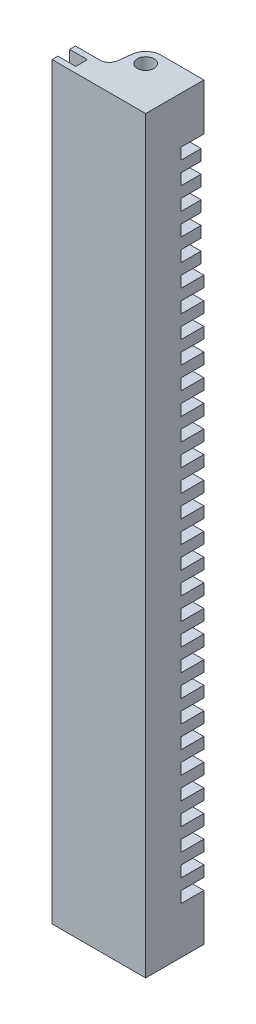
SolidWorks part; units mm, degrees
ref_plane "Front Plane" through (0, 0, 0) normal (0, 0, 1) x (1, 0, 0)
ref_plane "Top Plane" through (0, 0, 0) normal (0, 1, 0) x (1, 0, 0)
ref_plane "Right Plane" through (0, 0, 0) normal (1, 0, 0) x (0, 0, -1)
sketch "Sketch1" plane through (0, 0, 0) normal (0, 1, 0) x (1, 0, 0)
  line L0 (0, 0) -> (25.4, 0)
  line L1 (25.4, 0) -> (25.4, 25.4)
  line L2 (25.4, 25.4) -> (19.05, 25.4)
  line L3 (19.05, 25.4) -> (19.05, 6.35)
  line L4 (19.05, 6.35) -> (0, 6.35)
  line L5 (0, 6.35) -> (0, 0)
  dimension "D1" = 25.4
  dimension "D2" = 6.35
extrude "Boss-Extrude1" add sketch "Sketch1" along normal blind 203.2
sketch "Sketch2" plane through (0, 203.2, 0) normal (0, 1, 0) x (1, 0, 0)
  line L0 (19.05, 25.4) -> (19.05, 6.35) construction
  line L1 (19.05, 6.35) -> (0, 6.35) construction
  line L2 (19.05, 15.8022) -> (19.05, 6.35)
  line L3 (19.05, 6.35) -> (8.89, 6.35)
  line L4 (8.89, 6.35) -> (9.6295, 12.244)
  line L5 (19.05, 15.8022) -> (13.6618, 15.8022)
  line L6 (13.6618, 11.7382) -> (19.05, 6.35) construction
  arc A0 (13.6618, 15.8022) -> (9.6295, 12.244) centre (13.6618, 11.7382) ccw
  circle A1 centre (13.6618, 11.7382) radius 2.286
  dimension "D4" = 4.572
  dimension "D5" = 1.778
  dimension "D1" = 45
  dimension "D3" = 10.16
  dimension "D6" = 7.62
extrude "Boss-Extrude2" add sketch "Sketch2" against normal blind 6.35
ref_plane "Plane1" through (0, 101.6, 0) normal (0, 1, 0) x (1, 0, 0)
fillet "Fillet1" radius 2.54 1 edges at (8.89, 200.025, -6.35)
mirror "Mirror1" about plane through (0, 101.6, 0) normal (0, 1, 0) of "Fillet1", "Boss-Extrude2"
sketch "Sketch5" plane through (0, 203.2, 0) normal (0, 1, 0) x (1, 0, 0)
  line L0 (25.4, 0) -> (25.4, 25.4) construction
  line L1 (19.05, 25.4) -> (25.4, 25.4)
  line L2 (19.05, 25.4) -> (19.05, 15.8022)
  line L3 (19.05, 15.8022) -> (25.4, 15.8022)
  line L4 (25.4, 25.4) -> (25.4, 15.8022)
extrude "Cut-Extrude3" cut sketch "Sketch5" against normal through all
sketch "Sketch3" plane through (19.05, 0, 0) normal (-1, 0, 0) x (0, 0, 1)
  line L1 (-15.8022, 190.5) -> (-9.525, 190.5)
  line L2 (-15.8022, 190.5) -> (-15.8022, 187.452)
  line L3 (-15.8022, 187.452) -> (-9.525, 187.452)
  line L4 (-9.525, 190.5) -> (-9.525, 187.452)
  line L5 (-6.35, 196.85) -> (-6.35, 6.35) construction
  line L7 (-15.8022, 184.4741) -> (-15.8022, 181.4261)
  line L8 (-15.8022, 184.4741) -> (-9.525, 184.4741)
  line L9 (-9.525, 184.4741) -> (-9.525, 181.4261)
  line L10 (-15.8022, 181.4261) -> (-9.525, 181.4261)
  line L11 (-15.8022, 178.4481) -> (-15.8022, 175.4001)
  line L12 (-15.8022, 178.4481) -> (-9.525, 178.4481)
  line L13 (-9.525, 178.4481) -> (-9.525, 175.4001)
  line L14 (-15.8022, 175.4001) -> (-9.525, 175.4001)
  line L15 (-15.8022, 172.4222) -> (-15.8022, 169.3742)
  line L16 (-15.8022, 172.4222) -> (-9.525, 172.4222)
  line L17 (-9.525, 172.4222) -> (-9.525, 169.3742)
  line L18 (-15.8022, 169.3742) -> (-9.525, 169.3742)
  line L19 (-15.8022, 166.3963) -> (-15.8022, 163.3483)
  line L20 (-15.8022, 166.3963) -> (-9.525, 166.3963)
  line L21 (-9.525, 166.3963) -> (-9.525, 163.3483)
  line L22 (-15.8022, 163.3483) -> (-9.525, 163.3483)
  line L23 (-15.8022, 160.3703) -> (-15.8022, 157.3223)
  line L24 (-15.8022, 160.3703) -> (-9.525, 160.3703)
  line L25 (-9.525, 160.3703) -> (-9.525, 157.3223)
  line L26 (-15.8022, 157.3223) -> (-9.525, 157.3223)
  line L27 (-15.8022, 154.3444) -> (-15.8022, 151.2964)
  line L28 (-15.8022, 154.3444) -> (-9.525, 154.3444)
  line L29 (-9.525, 154.3444) -> (-9.525, 151.2964)
  line L30 (-15.8022, 151.2964) -> (-9.525, 151.2964)
  line L31 (-15.8022, 148.3185) -> (-15.8022, 145.2705)
  line L32 (-15.8022, 148.3185) -> (-9.525, 148.3185)
  line L33 (-9.525, 148.3185) -> (-9.525, 145.2705)
  line L34 (-15.8022, 145.2705) -> (-9.525, 145.2705)
  line L35 (-15.8022, 142.2926) -> (-15.8022, 139.2446)
  line L36 (-15.8022, 142.2926) -> (-9.525, 142.2926)
  line L37 (-9.525, 142.2926) -> (-9.525, 139.2446)
  line L38 (-15.8022, 139.2446) -> (-9.525, 139.2446)
  line L39 (-15.8022, 136.2666) -> (-15.8022, 133.2186)
  line L40 (-15.8022, 136.2666) -> (-9.525, 136.2666)
  line L41 (-9.525, 136.2666) -> (-9.525, 133.2186)
  line L42 (-15.8022, 133.2186) -> (-9.525, 133.2186)
  line L43 (-15.8022, 130.2407) -> (-15.8022, 127.1927)
  line L44 (-15.8022, 130.2407) -> (-9.525, 130.2407)
  line L45 (-9.525, 130.2407) -> (-9.525, 127.1927)
  line L46 (-15.8022, 127.1927) -> (-9.525, 127.1927)
  line L47 (-15.8022, 124.2148) -> (-15.8022, 121.1668)
  line L48 (-15.8022, 124.2148) -> (-9.525, 124.2148)
  line L49 (-9.525, 124.2148) -> (-9.525, 121.1668)
  line L50 (-15.8022, 121.1668) -> (-9.525, 121.1668)
  line L51 (-15.8022, 118.1888) -> (-15.8022, 115.1408)
  line L52 (-15.8022, 118.1888) -> (-9.525, 118.1888)
  line L53 (-9.525, 118.1888) -> (-9.525, 115.1408)
  line L54 (-15.8022, 115.1408) -> (-9.525, 115.1408)
  line L55 (-15.8022, 112.1629) -> (-15.8022, 109.1149)
  line L56 (-15.8022, 112.1629) -> (-9.525, 112.1629)
  line L57 (-9.525, 112.1629) -> (-9.525, 109.1149)
  line L58 (-15.8022, 109.1149) -> (-9.525, 109.1149)
  line L59 (-15.8022, 106.137) -> (-15.8022, 103.089)
  line L60 (-15.8022, 106.137) -> (-9.525, 106.137)
  line L61 (-9.525, 106.137) -> (-9.525, 103.089)
  line L62 (-15.8022, 103.089) -> (-9.525, 103.089)
  line L63 (-15.8022, 100.111) -> (-15.8022, 97.063)
  line L64 (-15.8022, 100.111) -> (-9.525, 100.111)
  line L65 (-9.525, 100.111) -> (-9.525, 97.063)
  line L66 (-15.8022, 97.063) -> (-9.525, 97.063)
  line L67 (-15.8022, 94.0851) -> (-15.8022, 91.0371)
  line L68 (-15.8022, 94.0851) -> (-9.525, 94.0851)
  line L69 (-9.525, 94.0851) -> (-9.525, 91.0371)
  line L70 (-15.8022, 91.0371) -> (-9.525, 91.0371)
  line L71 (-15.8022, 88.0592) -> (-15.8022, 85.0112)
  line L72 (-15.8022, 88.0592) -> (-9.525, 88.0592)
  line L73 (-9.525, 88.0592) -> (-9.525, 85.0112)
  line L74 (-15.8022, 85.0112) -> (-9.525, 85.0112)
  line L75 (-15.8022, 82.0332) -> (-15.8022, 78.9852)
  line L76 (-15.8022, 82.0332) -> (-9.525, 82.0332)
  line L77 (-9.525, 82.0332) -> (-9.525, 78.9852)
  line L78 (-15.8022, 78.9852) -> (-9.525, 78.9852)
  line L80 (-15.8022, 196.85) -> (-12.244, 196.85) construction
  line L81 (-15.8022, 6.35) -> (-15.8022, 196.85) construction
  line L82 (-15.8022, 76.0073) -> (-15.8022, 72.9593)
  line L83 (-15.8022, 76.0073) -> (-9.525, 76.0073)
  line L84 (-9.525, 76.0073) -> (-9.525, 72.9593)
  line L85 (-15.8022, 72.9593) -> (-9.525, 72.9593)
  line L86 (-15.8022, 69.9814) -> (-15.8022, 66.9334)
  line L87 (-15.8022, 69.9814) -> (-9.525, 69.9814)
  line L88 (-9.525, 69.9814) -> (-9.525, 66.9334)
  line L89 (-15.8022, 66.9334) -> (-9.525, 66.9334)
  line L90 (-15.8022, 63.9554) -> (-15.8022, 60.9074)
  line L91 (-15.8022, 63.9554) -> (-9.525, 63.9554)
  line L92 (-9.525, 63.9554) -> (-9.525, 60.9074)
  line L93 (-15.8022, 60.9074) -> (-9.525, 60.9074)
  line L94 (-15.8022, 57.9295) -> (-15.8022, 54.8815)
  line L95 (-15.8022, 57.9295) -> (-9.525, 57.9295)
  line L96 (-9.525, 57.9295) -> (-9.525, 54.8815)
  line L97 (-15.8022, 54.8815) -> (-9.525, 54.8815)
  line L98 (-15.8022, 51.9036) -> (-15.8022, 48.8556)
  line L99 (-15.8022, 51.9036) -> (-9.525, 51.9036)
  line L100 (-9.525, 51.9036) -> (-9.525, 48.8556)
  line L101 (-15.8022, 48.8556) -> (-9.525, 48.8556)
  line L102 (-15.8022, 45.8777) -> (-15.8022, 42.8297)
  line L103 (-15.8022, 45.8777) -> (-9.525, 45.8777)
  line L104 (-9.525, 45.8777) -> (-9.525, 42.8297)
  line L105 (-15.8022, 42.8297) -> (-9.525, 42.8297)
  line L106 (-15.8022, 39.8517) -> (-15.8022, 36.8037)
  line L107 (-15.8022, 39.8517) -> (-9.525, 39.8517)
  line L108 (-9.525, 39.8517) -> (-9.525, 36.8037)
  line L109 (-15.8022, 36.8037) -> (-9.525, 36.8037)
  line L110 (-15.8022, 33.8258) -> (-15.8022, 30.7778)
  line L111 (-15.8022, 33.8258) -> (-9.525, 33.8258)
  line L112 (-9.525, 33.8258) -> (-9.525, 30.7778)
  line L113 (-15.8022, 30.7778) -> (-9.525, 30.7778)
  line L114 (-15.8022, 27.7999) -> (-15.8022, 24.7519)
  line L115 (-15.8022, 27.7999) -> (-9.525, 27.7999)
  line L116 (-9.525, 27.7999) -> (-9.525, 24.7519)
  line L117 (-15.8022, 24.7519) -> (-9.525, 24.7519)
  line L118 (-15.8022, 21.7739) -> (-15.8022, 18.7259)
  line L119 (-15.8022, 21.7739) -> (-9.525, 21.7739)
  line L120 (-9.525, 21.7739) -> (-9.525, 18.7259)
  line L121 (-15.8022, 18.7259) -> (-9.525, 18.7259)
  line L122 (-15.8022, 15.748) -> (-15.8022, 12.7)
  line L123 (-15.8022, 15.748) -> (-9.525, 15.748)
  line L124 (-9.525, 15.748) -> (-9.525, 12.7)
  line L125 (-15.8022, 12.7) -> (-9.525, 12.7)
  line L126 (-12.244, 6.35) -> (-15.8022, 6.35) construction
  dimension "D1" = 3.175
  dimension "D2" = 3.048
  dimension "D3" = 6.35
  dimension "D5" = 6.35
  dimension "D4" = 30
extrude "Cut-Extrude1" cut sketch "Sketch3" against normal through all
sketch "Sketch4" plane through (0, 0, 0) normal (0, -1, 0) x (1, 0, 0)
  line L0 (0, -6.35) -> (0, 0) construction
  line L1 (0, -1.5875) -> (4.826, -1.5875)
  line L2 (0, -1.5875) -> (0, -4.7625)
  line L3 (0, -4.7625) -> (4.826, -4.7625)
  line L4 (4.826, -1.5875) -> (4.826, -4.7625)
  point P6 (0, -3.175)
  point P7 (0, -3.175)
  dimension "D1" = 3.175
  dimension "D2" = 4.826
extrude "Cut-Extrude2" cut sketch "Sketch4" against normal through all
chamfer "Chamfer1" distance 0.762 angle 45 20 edges at (25.4, 161.8593, -15.8022) (25.4, 167.8852, -15.8022) (25.4, 173.9112, -15.8022) (25.4, 179.9371, -15.8022) (25.4, 185.963, -15.8022) (19.05, 161.8593, -15.8022) (19.05, 167.8852, -15.8022) (19.05, 173.9112, -15.8022) (19.05, 179.9371, -15.8022) (19.05, 185.963, -15.8022) (22.225, 187.452, -15.8022) (22.225, 160.3703, -15.8022) (22.225, 166.3963, -15.8022) (22.225, 163.3483, -15.8022) (22.225, 184.4741, -15.8022) (22.225, 181.4261, -15.8022) (22.225, 178.4481, -15.8022) (22.225, 175.4001, -15.8022) (22.225, 172.4222, -15.8022) (22.225, 169.3742, -15.8022)
